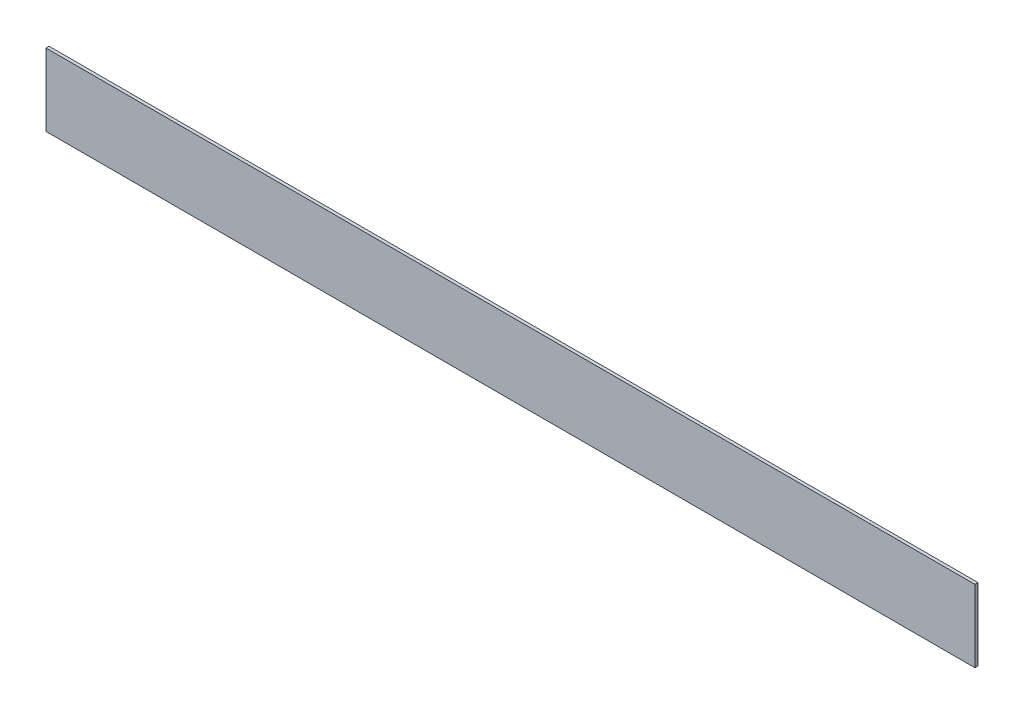
SolidWorks part; units mm, degrees
ref_plane "Plan de face" through (0, 0, 0) normal (0, 0, 1) x (1, 0, 0)
ref_plane "Plan de dessus" through (0, 0, 0) normal (0, 1, 0) x (1, 0, 0)
ref_plane "Plan de droite" through (0, 0, 0) normal (1, 0, 0) x (0, 0, -1)
sketch "Esquisse1" plane through (0, 0, 0) normal (0, 0, 1) x (1, 0, 0)
  line L1 (-202.9539, 33.3934) -> (247.0461, 33.3934)
  line L2 (-202.9539, 33.3934) -> (-202.9539, -1.6066)
  line L3 (-202.9539, -1.6066) -> (247.0461, -1.6066)
  line L4 (247.0461, 33.3934) -> (247.0461, -1.6066)
  dimension "D1" = 450
  dimension "D2" = 35
extrude "Boss.-Extru.1" add sketch "Esquisse1" along normal blind 1.5
